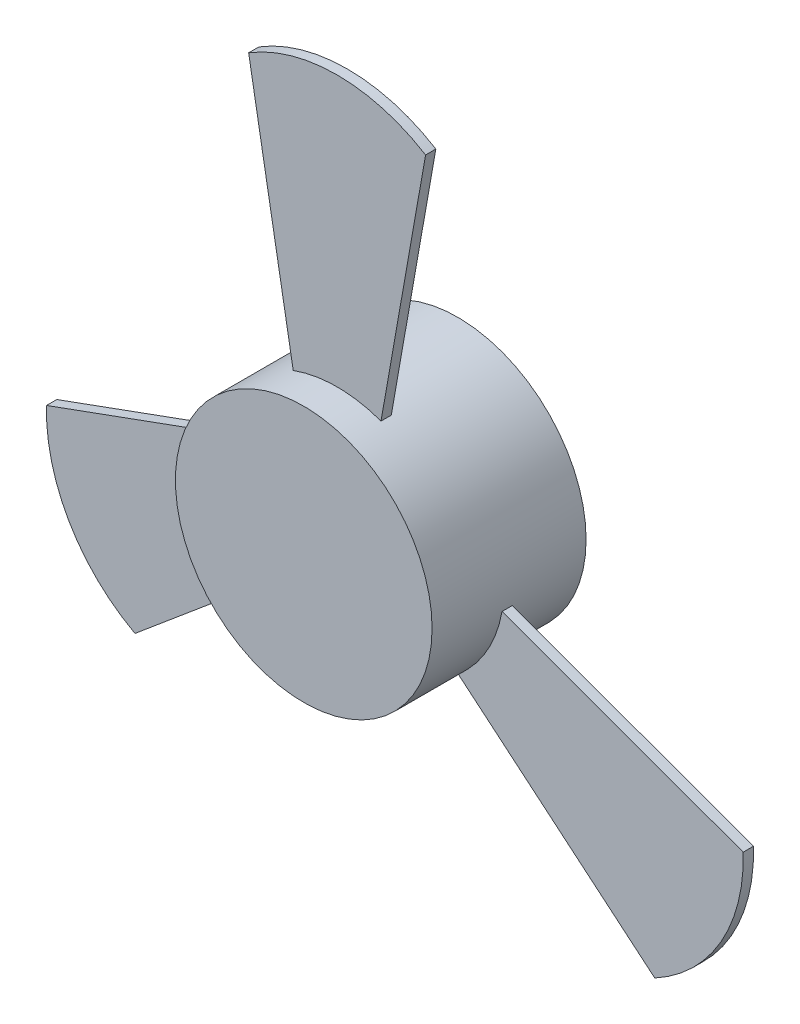
SolidWorks part; units mm, degrees
ref_plane "Front Plane" through (0, 0, 0) normal (0, 0, 1) x (1, 0, 0)
ref_plane "Top Plane" through (0, 0, 0) normal (0, 1, 0) x (1, 0, 0)
ref_plane "Right Plane" through (0, 0, 0) normal (1, 0, 0) x (0, 0, -1)
sketch "Sketch1" plane through (0, 0, 0) normal (0, 0, 1) x (1, 0, 0)
  circle A0 centre (0, 0) radius 50
  dimension "D1" = 100
extrude "Boss-Extrude1" add sketch "Sketch1" along normal blind 60
sketch "Sketch2" plane through (0, 0, 0) normal (0, 0, 1) x (1, 0, 0)
  line L0 (0, 0) -> (0, 153.9372) construction
  line L1 (-21.5108, 45.1363) -> (-38.8756, 143.6171)
  line L3 (38.8756, 143.6171) -> (21.5108, 45.1363)
  arc A0 (-21.5108, 45.1363) -> (21.5108, 45.1363) centre (0, 0) cw
  circle A1 centre (0, 0) radius 50 construction
  arc A2 (-38.8756, 143.6171) -> (38.8756, 143.6171) centre (0, 73.0513) cw
  point P10 (0, 153.6171)
  point P24 (0, 0)
  dimension "D1" = 20
  dimension "D2" = 100
  dimension "D3" = 100
  dimension "D4" = 10
extrude "Boss-Extrude2" [suppressed] add sketch "Sketch2" along normal mid plane 20
sketch "Sketch3" [suppressed] plane through (0, 0, 10) normal (0, 0, 1) x (1, 0, 0)
  line L0 (0, 0) -> (0, 164.8058) construction
  circle A0 centre (0, 135) radius 5
  dimension "D1" = 10
  dimension "D2" = 135
extrude "Boss-Extrude3" [suppressed] add sketch "Sketch3" along normal mid plane 2
sketch3d "3DSketch3" plane through (0, 0, 0) normal (0, 0, 1) x (1, 0, 0)
  dimension "D1" = 15
  dimension "D2" = 30
  dimension "D3" = 45
sketch "Sketch4" plane through (0, 0, 45) normal (0, 0, -1) x (-1, 0, 0)
  line L0 (0, 0) -> (0, 100) construction
  line L1 (-17.101, 46.9846) -> (-34.4658, 145.4654)
  line L2 (17.101, 46.9846) -> (34.4658, 145.4654)
  arc A0 (-17.101, 46.9846) -> (17.101, 46.9846) centre (0, 0) cw
  circle A1 centre (0, 0) radius 50 construction
  arc A2 (-34.4658, 145.4654) -> (34.4658, 145.4654) centre (0, 89.6509) cw
  dimension "D1" = 10
  dimension "D2" = 100
extrude "Boss-Extrude4" add sketch "Sketch4" along normal mid plane 4
sketch "Sketch5" plane through (0, 0, 30) normal (0, 0, -1) x (-1, 0, 0)
  line L0 (-32.1394, -38.3022) -> (-108.7438, -102.581)
  line L1 (-49.2404, -8.6824) -> (-143.2096, -42.8844)
  arc A0 (-32.1394, -38.3022) -> (-49.2404, -8.6824) centre (0, 0) cw
  arc A1 (-108.7438, -102.581) -> (-143.2096, -42.8844) centre (-77.6399, -44.8254) cw
extrude "Boss-Extrude5" add sketch "Sketch5" along normal mid plane 4
sketch "Sketch6" plane through (0, 0, 15) normal (0, 0, -1) x (-1, 0, 0)
  line L0 (49.2404, -8.6824) -> (143.2096, -42.8844)
  line L1 (32.1394, -38.3022) -> (108.7438, -102.581)
  arc A0 (49.2404, -8.6824) -> (32.1394, -38.3022) centre (0, 0) cw
  arc A1 (143.2096, -42.8844) -> (108.7438, -102.581) centre (77.6399, -44.8254) cw
extrude "Boss-Extrude6" add sketch "Sketch6" along normal mid plane 4
